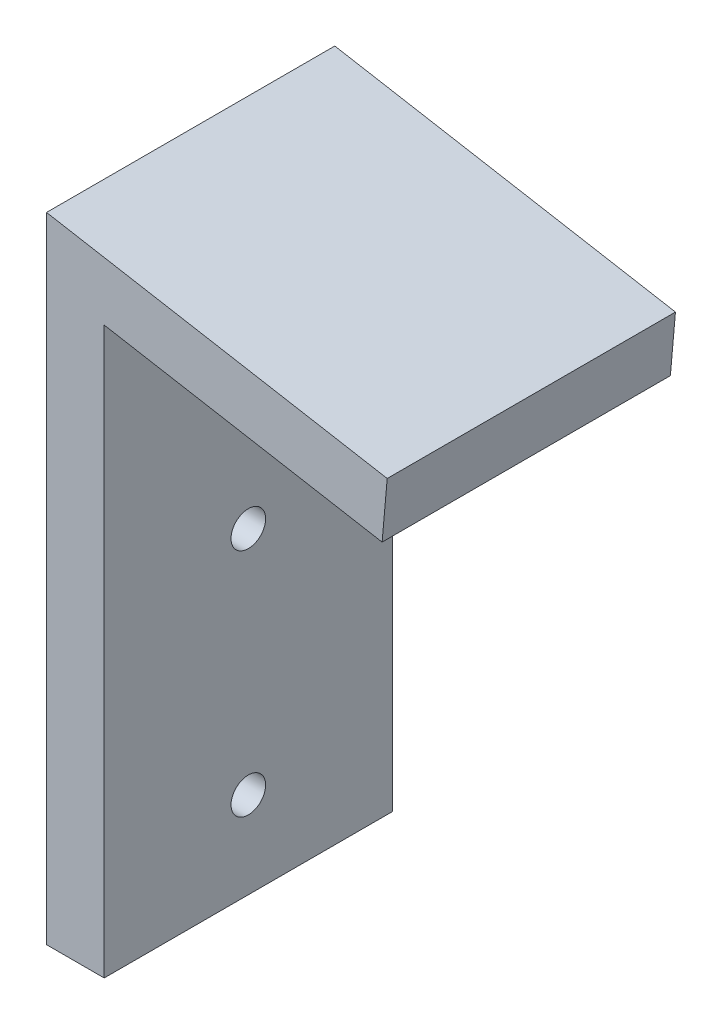
SolidWorks part; units mm, degrees
ref_plane "Plan de face" through (0, 0, 0) normal (0, 0, 1) x (1, 0, 0)
ref_plane "Plan de dessus" through (0, 0, 0) normal (0, 1, 0) x (1, 0, 0)
ref_plane "Plan de droite" through (0, 0, 0) normal (1, 0, 0) x (0, 0, -1)
sketch "Esquisse1" plane through (0, 0, 0) normal (0, 0, 1) x (1, 0, 0)
  line L0 (0, 0) -> (0, -110)
  line L1 (0, -110) -> (10, -110)
  line L2 (10, -110) -> (10, -11.9175)
  line L3 (10, -11.9175) -> (58.2068, -20.4177)
  line L4 (58.2068, -20.4177) -> (59.0885, -10.4189)
  line L5 (59.0885, -10.4189) -> (0, 0)
  dimension "D1" = 10
  dimension "D2" = 10
  dimension "D3" = 60
  dimension "D4" = 110
  dimension "D5" = 80
extrude "Boss.-Extru.1" add sketch "Esquisse1" along normal blind 50
sketch "Esquisse2" plane through (0, 0, 0) normal (-1, 0, 0) x (0, 0, 1)
  line L1 (50, 0) -> (50, -110) construction
  line L2 (50, 0) -> (0, 0) construction
  circle A0 centre (25, -95) radius 3
  circle A1 centre (25, -55) radius 3
  dimension "D1" = 6
  dimension "D2" = 40
  dimension "D3" = 55
  dimension "D4" = 25
  dimension "D5" = 25
extrude "Enlèv. mat.-Extru.1" cut sketch "Esquisse2" against normal blind 10
